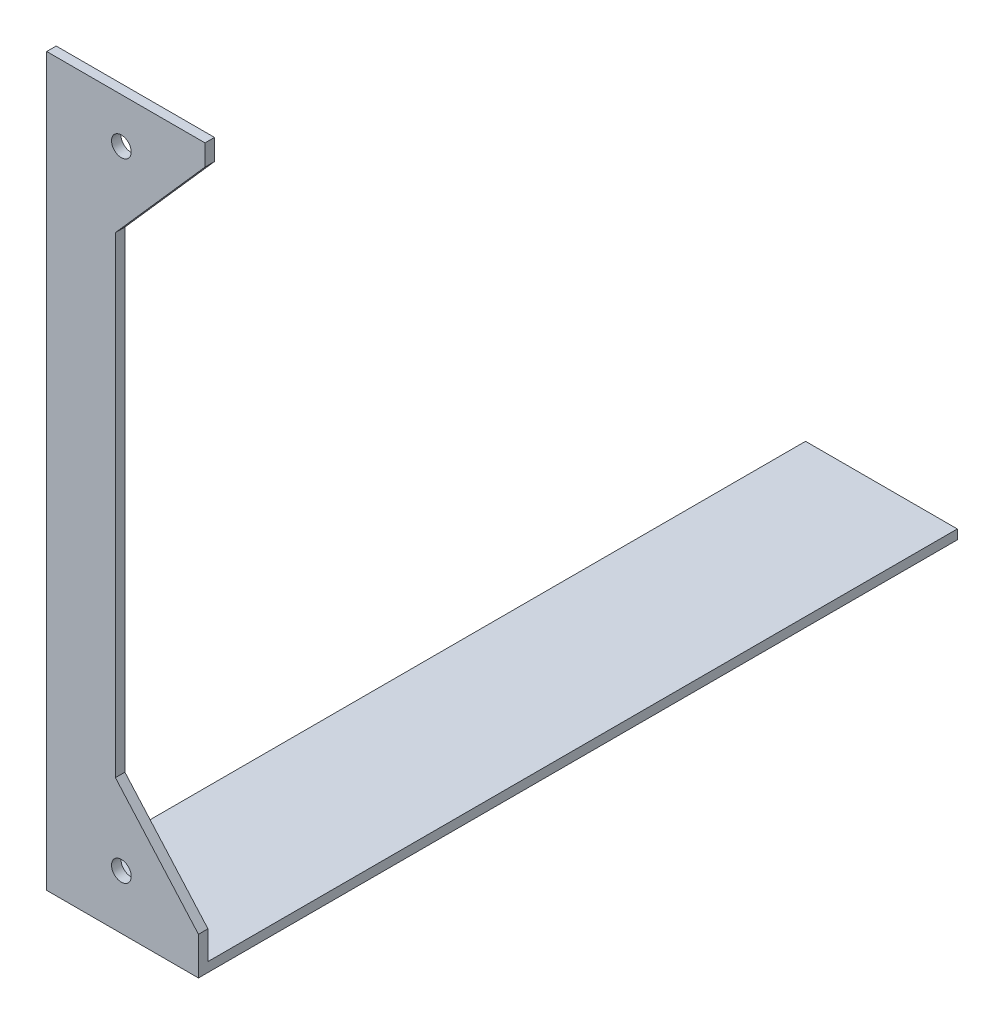
SolidWorks part; units mm, degrees
ref_plane "Front Plane" through (0, 0, 0) normal (0, 0, 1) x (1, 0, 0)
ref_plane "Top Plane" through (0, 0, 0) normal (0, 1, 0) x (1, 0, 0)
ref_plane "Right Plane" through (0, 0, 0) normal (1, 0, 0) x (0, 0, -1)
sketch "Sketch1" plane through (0, 0, 0) normal (0, 0, 1) x (1, 0, 0)
  line L0 (-250, 120) -> (0, 120) construction
  line L1 (-238.5, 99.5) -> (-223.5, 116.5) construction
  line L2 (-244.6, 99.5) -> (-238.5, 99.5) construction
  line L3 (-244.6, 20.5) -> (-244.6, 99.5) construction
  line L4 (-250, 2) -> (-250, 118) construction
  line L5 (0, 0) -> (-250, 0) construction
  line L6 (-238.5, 20.5) -> (-244.6, 20.5) construction
  line L7 (-223.5, 3.5) -> (-238.5, 20.5) construction
  line L8 (-250, 120) -> (-223.5, 120)
  line L9 (-238.5, 99.5) -> (-223.5, 116.5)
  line L10 (-244.6, 99.5) -> (-238.5, 99.5)
  line L11 (-244.6, 20.5) -> (-244.6, 99.5)
  line L12 (-250, 0) -> (-250, 120)
  line L13 (-223.5, 0) -> (-250, 0)
  line L14 (-238.5, 20.5) -> (-244.6, 20.5)
  line L15 (-223.5, 3.5) -> (-238.5, 20.5)
  line L16 (-223.5, 116.5) -> (-223.5, 120)
  line L17 (-223.5, 3.5) -> (-223.5, 0)
  line L18 (-238.5, 20.5) -> (-238.5, 99.5)
  line L19 (-224.6, 4.7467) -> (-224.6, 0)
  arc A0 (-239.15, 112.5) -> (-235.85, 112.5) centre (-237.5, 112.5) ccw construction
  arc A1 (-235.85, 112.5) -> (-239.15, 112.5) centre (-237.5, 112.5) ccw construction
  arc A2 (-235.85, 7.5) -> (-239.15, 7.5) centre (-237.5, 7.5) ccw construction
  arc A3 (-239.15, 7.5) -> (-235.85, 7.5) centre (-237.5, 7.5) ccw construction
  arc A4 (-239.15, 112.5) -> (-235.85, 112.5) centre (-237.5, 112.5) ccw
  arc A5 (-235.85, 112.5) -> (-239.15, 112.5) centre (-237.5, 112.5) ccw
  arc A6 (-235.85, 7.5) -> (-239.15, 7.5) centre (-237.5, 7.5) ccw
  arc A7 (-239.15, 7.5) -> (-235.85, 7.5) centre (-237.5, 7.5) ccw
  dimension "D1" = 25.4
extrude "Boss-Extrude1" add sketch "Sketch1" along normal blind 1.5875 contours L14 L18 L10 L11 | L17 L15 L14 L11 L10 L9 L16 L8 L12 L13 A7 A6 A5 A4
sketch "Sketch2" plane through (0, 0, 0) normal (0, 1, 0) x (1, 0, 0)
  line L1 (-250, -1.5875) -> (-250, 125.4125)
  line L2 (-250, 125.4125) -> (-224.6, 125.4125)
  line L3 (-224.6, 125.4125) -> (-224.6, -1.5875)
  line L4 (-224.6, -1.5875) -> (-250, -1.5875) construction
  line L5 (-224.6, -1.5875) -> (-250, -1.5875)
  point P5 (-223.5, -1.5875)
  point P7 (0, 0)
  point P8 (-217.7772, -2.0783)
  point P10 (-224.6, -2.2766)
  dimension "D1" = 127
extrude "Boss-Extrude2" add sketch "Sketch2" against normal blind 1.5875 contours L3 L5 L1 L2
